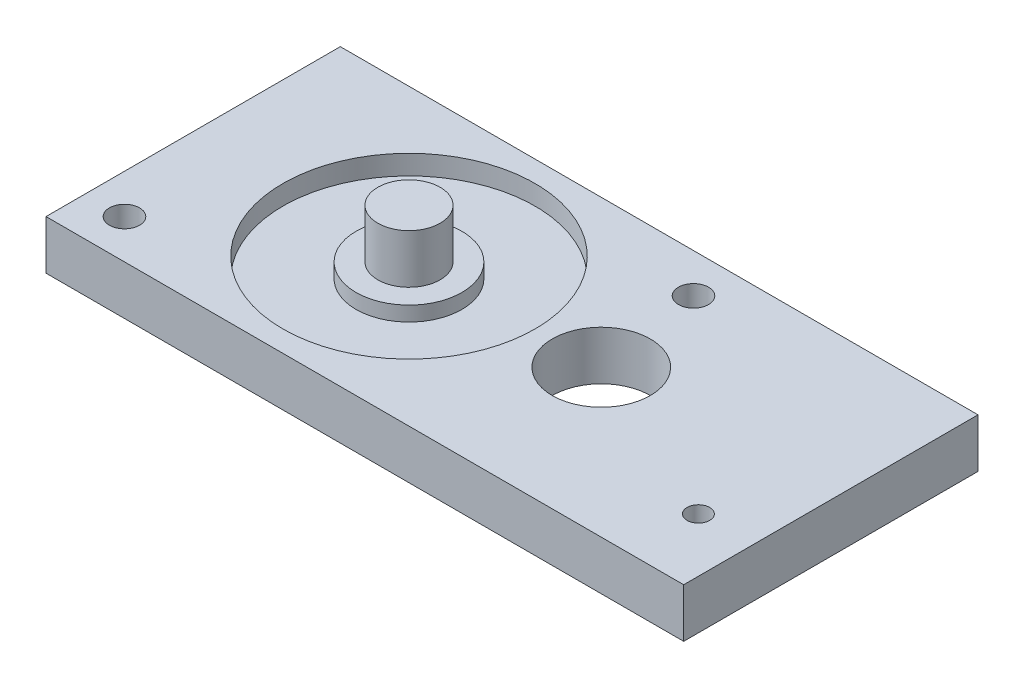
SolidWorks part; units mm, degrees
ref_plane "Front" through (0, 0, 0) normal (0, 0, 1) x (1, 0, 0)
ref_plane "Top" through (0, 0, 0) normal (0, 1, 0) x (1, 0, 0)
ref_plane "Right" through (0, 0, 0) normal (1, 0, 0) x (0, 0, -1)
sketch "Sketch1" plane through (0, 0, 0) normal (0, 1, 0) x (1, 0, 0)
  line L0 (-22, -15) -> (35, -15)
  line L1 (-22, 15) -> (35, 15)
  line L2 (-22, 15) -> (-22, -15)
  line L3 (35, 15) -> (35, -15)
  dimension "D1" = 30
extrude "Boss-Extrude1" add sketch "Sketch1" along normal blind 5
sketch "Sketch2" plane through (0, 5, 0) normal (0, 1, 0) x (1, 0, 0)
  circle A0 centre (0, 0) radius 3.175
  dimension "D1" = 6.35
extrude "Boss-Extrude2" add sketch "Sketch2" along normal blind 4.5
sketch "Sketch3" plane through (0, 5, 0) normal (0, 1, 0) x (1, 0, 0)
  circle A0 centre (-18, -11) radius 1.5367
  circle A1 centre (18, 11) radius 1.5367
  dimension "D5" = 3.0734
  dimension "D1" = 18
  dimension "D2" = 11
  dimension "D3" = 11
  dimension "D4" = 18
extrude "Cut-Extrude1" cut sketch "Sketch3" against normal blind 5
sketch "Sketch4" plane through (0, 5, 0) normal (0, 1, 0) x (1, 0, 0)
  circle A0 centre (0, 0) radius 5.4
  circle A1 centre (0, 0) radius 12.85
  dimension "D1" = 25.7
  dimension "D2" = 10.8
extrude "Cut-Extrude2" cut sketch "Sketch4" against normal blind 2
sketch "Sketch5" plane through (0, 5, 0) normal (0, 1, 0) x (1, 0, 0)
  circle A0 centre (19.6, 0) radius 5
  dimension "D2" = 10
  dimension "D1" = 19.6
extrude "Cut-Extrude3" cut sketch "Sketch5" against normal blind 10
sketch "Sketch6" plane through (0, 5, 0) normal (0, 1, 0) x (1, 0, 0)
  line L0 (-22, -15) -> (35, -15) construction
  line L1 (35, 15) -> (43, 15)
  line L2 (35, 15) -> (35, -15)
  line L3 (35, -15) -> (43, -15)
  line L4 (43, 15) -> (43, -15)
  dimension "D1" = 8
extrude "Boss-Extrude3" add sketch "Sketch6" against normal blind 5
sketch "Sketch7" plane through (0, 5, 0) normal (0, 1, 0) x (1, 0, 0)
  circle A0 centre (0, 0) radius 3.175
  circle A1 centre (0, 0) radius 5.4
  circle A2 centre (0, 0) radius 5.4 construction
  circle A3 centre (0, 0) radius 3.175 construction
extrude "Cut-Extrude4" cut sketch "Sketch7" against normal blind 0.5
sketch "Sketch8" plane through (0, 5, 0) normal (0, 1, 0) x (1, 0, 0)
  line L0 (-22, -15) -> (43, -15) construction
  line L1 (43, -15) -> (43, 15) construction
  circle A0 centre (37.5, -8) radius 1.15
  dimension "D1" = 2.3
  dimension "D2" = 7
  dimension "D3" = 5.5
extrude "Cut-Extrude5" cut sketch "Sketch8" against normal blind 15
